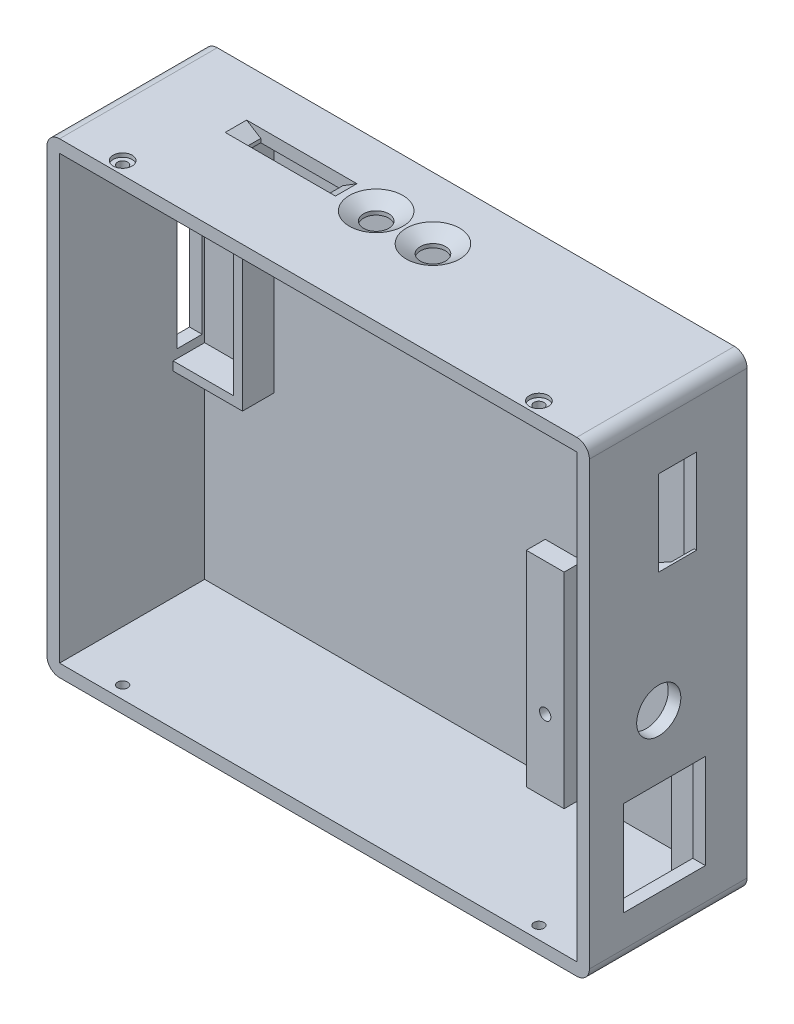
SolidWorks part; units mm, degrees
ref_plane "Front Plane" through (0, 0, 0) normal (0, 0, 1) x (1, 0, 0)
ref_plane "Top Plane" through (0, 0, 0) normal (0, 1, 0) x (1, 0, 0)
ref_plane "Right Plane" through (0, 0, 0) normal (1, 0, 0) x (0, 0, -1)
sketch "Sketch1" plane through (0, 0, 0) normal (0, 0, 1) x (1, 0, 0)
  line L1 (0, 0) -> (86, 0)
  line L2 (0, 0) -> (0, 74)
  line L3 (0, 74) -> (86, 74)
  line L4 (86, 0) -> (86, 74)
  dimension "D1" = 74
  dimension "D2" = 86
extrude "Boss-Extrude1" add sketch "Sketch1" along normal blind 25
sketch "Sketch3" plane through (0, 0, 25) normal (0, 0, 1) x (1, 0, 0)
  line L0 (0, 74) -> (0, 0) construction
  line L1 (2, 72) -> (84, 72)
  line L2 (2, 72) -> (2, 2)
  line L3 (2, 2) -> (84, 2)
  line L4 (84, 72) -> (84, 2)
  line L5 (86, 74) -> (0, 74) construction
  line L6 (0, 0) -> (86, 0) construction
  line L7 (86, 0) -> (86, 74) construction
  dimension "D1" = 2
  dimension "D2" = 2
  dimension "D3" = 2
  dimension "D4" = 2
extrude "Cut-Extrude1" cut sketch "Sketch3" against normal blind 23
sketch "Sketch4" plane through (0, 0, 2) normal (0, 0, 1) x (1, 0, 0)
  line L0 (84, 72) -> (2, 72) construction
  line L1 (84, 72) -> (76, 72)
  line L2 (84, 72) -> (84, 34.5)
  line L3 (84, 34.5) -> (76, 34.5)
  line L4 (76, 72) -> (76, 34.5)
  line L5 (13, 72) -> (11.6, 72)
  line L6 (13, 72) -> (13, 34.5)
  line L7 (13, 34.5) -> (11.6, 34.5)
  line L8 (11.6, 72) -> (11.6, 34.5)
  line L9 (84, 2) -> (84, 72) construction
  dimension "D1" = 37.5
  dimension "D2" = 8
  dimension "D3" = 71
  dimension "D4" = 1.4
extrude "Boss-Extrude2" add sketch "Sketch4" along normal blind 5
sketch "Sketch5" plane through (0, 0, 7) normal (0, 0, 1) x (1, 0, 0)
  line L0 (76, 72) -> (76, 34.5) construction
  line L1 (76, 54) -> (79, 54)
  line L2 (76, 54) -> (76, 62)
  line L3 (76, 62) -> (79, 62)
  line L4 (79, 54) -> (79, 62)
  line L5 (84, 72) -> (76, 72) construction
  line L6 (84, 34.5) -> (84, 72) construction
  line L7 (76, 34.5) -> (84, 34.5) construction
  line L8 (76, 41.5) -> (77, 41.5)
  line L9 (76, 41.5) -> (76, 45.5)
  line L10 (76, 45.5) -> (77, 45.5)
  line L11 (77, 41.5) -> (77, 45.5)
  dimension "D1" = 8
  dimension "D2" = 18
  dimension "D3" = 5
  dimension "D4" = 7
  dimension "D5" = 7
  dimension "D6" = 4
extrude "Cut-Extrude2" cut sketch "Sketch5" against normal blind 2
sketch "Sketch6" plane through (0, 0, 7) normal (0, 0, 1) x (1, 0, 0)
  line L0 (84, 72) -> (76, 72) construction
  line L2 (84, 34.5) -> (84, 72) construction
  circle A0 centre (80, 67.25) radius 1
  circle A1 centre (80, 39.25) radius 1
  dimension "D4" = 2
  dimension "D5" = 2
  dimension "D1" = 28
  dimension "D2" = 4.75
  dimension "D3" = 4
extrude "Cut-Extrude3" cut sketch "Sketch6" against normal blind 5
sketch "Sketch7" plane through (2, 0, 0) normal (1, 0, 0) x (0, 0, -1)
  line L1 (-2.4, 70.85) -> (-6.4, 70.85)
  line L2 (-2.4, 70.85) -> (-2.4, 35.85)
  line L3 (-2.4, 35.85) -> (-6.4, 35.85)
  line L4 (-6.4, 70.85) -> (-6.4, 35.85)
  line L5 (-2, 72) -> (-2, 2) construction
  line L6 (-2, 72) -> (-25, 72) construction
  dimension "D1" = 4
  dimension "D2" = 35
  dimension "D3" = 0.4
  dimension "D4" = 1.15
extrude "Cut-Extrude4" cut sketch "Sketch7" against normal blind 5
sketch "Sketch8" plane through (84, 0, 0) normal (-1, 0, 0) x (0, 0, 1)
  line L0 (8, 72) -> (8, 34.2936) construction
  line L1 (7, 72) -> (25, 72) construction
  line L2 (7, 34.5) -> (7, 72) construction
  line L3 (7, 34.5) -> (2, 34.5) construction
  line L4 (8, 64.5) -> (14, 64.5)
  line L5 (8, 64.5) -> (8, 41)
  line L6 (8, 41) -> (14, 41)
  line L7 (14, 64.5) -> (14, 41)
  dimension "D1" = 1
  dimension "D2" = 6
  dimension "D3" = 31
  dimension "D4" = 30
extrude "Cut-Extrude5" cut sketch "Sketch8" against normal blind 5
sketch "Sketch9" plane through (0, 0, 2) normal (0, 0, 1) x (1, 0, 0)
  line L0 (2, 2) -> (84, 2) construction
  line L1 (84, 34.5) -> (79, 34.5)
  line L2 (84, 34.5) -> (84, 2)
  line L3 (84, 2) -> (79, 2)
  line L4 (79, 34.5) -> (79, 2)
  line L6 (62, 2) -> (56, 2)
  line L7 (62, 2) -> (62, 34.5)
  line L8 (62, 34.5) -> (56, 34.5)
  line L9 (56, 2) -> (56, 34.5)
  dimension "D1" = 5
  dimension "D2" = 6
  dimension "D3" = 22
extrude "Boss-Extrude3" add sketch "Sketch9" along normal blind 3
sketch "Sketch10" plane through (0, 0, 5) normal (0, 0, 1) x (1, 0, 0)
  line L0 (84, 2) -> (84, 34.5) construction
  line L1 (56, 2) -> (62, 2) construction
  circle A0 centre (59, 13.5) radius 0.9
  dimension "D3" = 1.8
  dimension "D1" = 25
  dimension "D2" = 11.5
extrude "Cut-Extrude6" cut sketch "Sketch10" against normal blind 4
sketch "Sketch11" plane through (84, 0, 0) normal (-1, 0, 0) x (0, 0, 1)
  line L0 (6.6, 33.2649) -> (6.6, 4.1124) construction
  line L1 (5, 2) -> (5, 34.5) construction
  line L2 (5, 2) -> (25, 2) construction
  line L3 (6.6, 22) -> (19.6, 22)
  line L4 (6.6, 22) -> (6.6, 7)
  line L5 (6.6, 7) -> (19.6, 7)
  line L6 (19.6, 22) -> (19.6, 7)
  dimension "D1" = 1.6
  dimension "D2" = 15
  dimension "D3" = 13
  dimension "D4" = 20
extrude "Cut-Extrude7" cut sketch "Sketch11" against normal blind 4
fillet "Fillet1" radius 2 4 edges at (86, 74, 12.5) (0, 74, 12.5) (0, 0, 12.5) (86, 0, 12.5)
sketch "Sketch12" plane through (84, 0, 0) normal (-1, 0, 0) x (0, 0, 1)
  line L0 (25, 2) -> (25, 72) construction
  line L1 (7, 72) -> (25, 72) construction
  circle A0 centre (14, 32) radius 3.5
  dimension "D1" = 7
  dimension "D2" = 11
  dimension "D3" = 40
extrude "Cut-Extrude8" cut sketch "Sketch12" against normal blind 4
sketch "Sketch13" plane through (0, 72, 0) normal (0, -1, 0) x (-1, 0, 0)
  line L0 (-80.7121, -7.6) -> (-14.4298, -7.6) construction
  line L1 (-84, -7) -> (-76, -7) construction
  line L2 (-84, -7) -> (-84, -25) construction
  line L3 (-29.5, -7.6) -> (-16.5, -7.6)
  line L4 (-29.5, -7.6) -> (-29.5, -11)
  line L5 (-29.5, -11) -> (-16.5, -11)
  line L6 (-16.5, -7.6) -> (-16.5, -11)
  circle A0 centre (-37, -9.8) radius 2
  circle A1 centre (-46, -9.8) radius 2
  dimension "D5" = 4
  dimension "D6" = 4
  dimension "D1" = 0.6
  dimension "D2" = 13
  dimension "D3" = 67.5
  dimension "D4" = 3.4
  dimension "D7" = 9
  dimension "D8" = 47
  dimension "D9" = 2.8
  dimension "D10" = 2.8
extrude "Cut-Extrude9" cut sketch "Sketch13" against normal blind 4
chamfer "Chamfer1" distance 1.4 angle 58 4 edges at (29.5, 74, 9.3) (16.5, 74, 9.3) (37, 74, 7.8) (46, 74, 7.8)
sketch "Sketch14" plane through (0, 0, 0) normal (0, -1, 0) x (-1, 0, 0)
  line L0 (0, 0) -> (0, -25) construction
  line L1 (-86, -25) -> (-86, 0) construction
  line L2 (-2, -25) -> (-84, -25) construction
  circle A0 centre (-10, -23) radius 0.8
  circle A1 centre (-76, -23) radius 0.8
  dimension "D5" = 1.6
  dimension "D6" = 1.6
  dimension "D1" = 10
  dimension "D2" = 10
  dimension "D3" = 2
  dimension "D4" = 2
extrude "Cut-Extrude10" cut sketch "Sketch14" against normal blind 76
sketch "Sketch15" plane through (0, 0, 0) normal (0, -1, 0) x (-1, 0, 0)
  circle A0 centre (-10, -23) radius 1.5
  circle A1 centre (-76, -23) radius 1.5
  dimension "D1" = 3
  dimension "D2" = 3
extrude "Cut-Extrude11" cut sketch "Sketch15" against normal blind 0.6
sketch "Sketch16" plane through (0, 74, 0) normal (0, 1, 0) x (1, 0, 0)
  circle A0 centre (76, -23) radius 1.5
  circle A1 centre (10, -23) radius 1.5
  dimension "D1" = 3
  dimension "D2" = 3
extrude "Cut-Extrude12" cut sketch "Sketch16" against normal blind 0.6
sketch "Sketch17" plane through (0, 0, 14) normal (0, 0, -1) x (-1, 0, 0)
  line L0 (-86, 41) -> (-86, 64.5) construction
  line L1 (-84, 41) -> (-86, 41)
  line L2 (-84, 41) -> (-84, 51)
  line L3 (-84, 51) -> (-86, 51)
  line L4 (-86, 41) -> (-86, 51)
  dimension "D1" = 10
extrude "Boss-Extrude4" add sketch "Sketch17" along normal blind 2.4
sketch "Sketch18" plane through (86, 0, 0) normal (1, 0, 0) x (0, 0, -1)
  line L1 (-11.6, 51) -> (-8, 51)
  line L2 (-11.6, 51) -> (-11.6, 41)
  line L3 (-11.6, 41) -> (-8, 41)
  line L4 (-8, 51) -> (-8, 41)
extrude "Boss-Extrude5" add sketch "Sketch18" against normal blind 0.4
chamfer "Chamfer2" distance 2 angle 38 1 edges at (84, 46, 11.6)
sketch "Sketch20" plane through (0, 0, 2) normal (0, 0, 1) x (1, 0, 0)
  line L0 (2, 72) -> (2, 2) construction
  line L1 (13, 34.5) -> (2, 34.5)
  line L2 (13, 34.5) -> (13, 33.1)
  line L3 (13, 33.1) -> (2, 33.1)
  line L4 (2, 34.5) -> (2, 33.1)
  dimension "D1" = 1.4
extrude "Boss-Extrude6" add sketch "Sketch20" along normal blind 5
